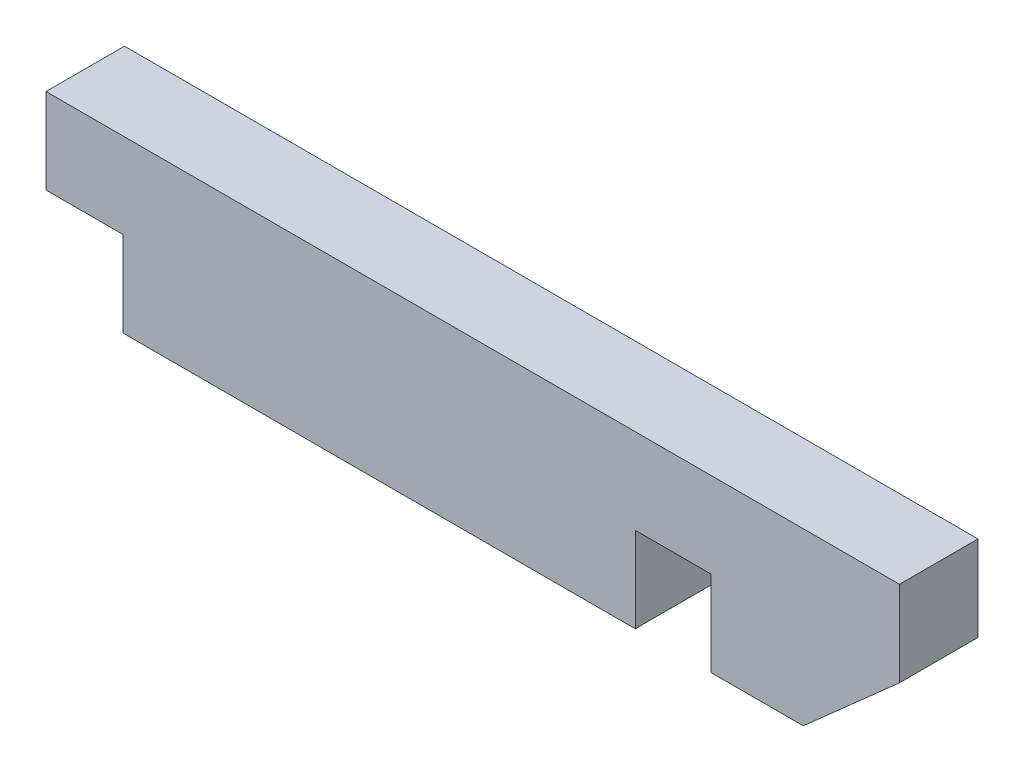
SolidWorks part; units mm, degrees
ref_plane "Front Plane" through (0, 0, 0) normal (0, 0, 1) x (1, 0, 0)
ref_plane "Top Plane" through (0, 0, 0) normal (0, 1, 0) x (1, 0, 0)
ref_plane "Right Plane" through (0, 0, 0) normal (1, 0, 0) x (0, 0, -1)
sketch "Sketch1" plane through (0, 0, 0) normal (0, 0, 1) x (1, 0, 0)
  line L0 (36.478, 0) -> (43.336, 0)
  line L1 (-7.264, 0) -> (30.836, 0)
  line L2 (-13.006, 6.35) -> (-13.006, 12.7)
  line L3 (-13.006, 12.7) -> (50.494, 12.7)
  line L4 (50.494, 6.35) -> (50.494, 12.7)
  line L5 (50.494, 6.35) -> (43.336, 0)
  line L6 (30.836, 0) -> (30.836, 6.35)
  line L7 (-13.006, 6.35) -> (-7.264, 6.35)
  line L8 (-7.264, 0) -> (-7.264, 6.35)
  line L9 (30.836, 6.35) -> (36.478, 6.35)
  line L10 (36.478, 0) -> (36.478, 6.35)
  dimension "D1" = 6.35
  dimension "D2" = 5.742
  dimension "D3" = 6.35
  dimension "D4" = 63.5
  dimension "D5" = 5.642
  dimension "D6" = 6.35
  dimension "D7" = 38.1
extrude "Boss-Extrude1" add sketch "Sketch1" along normal blind 5.842
